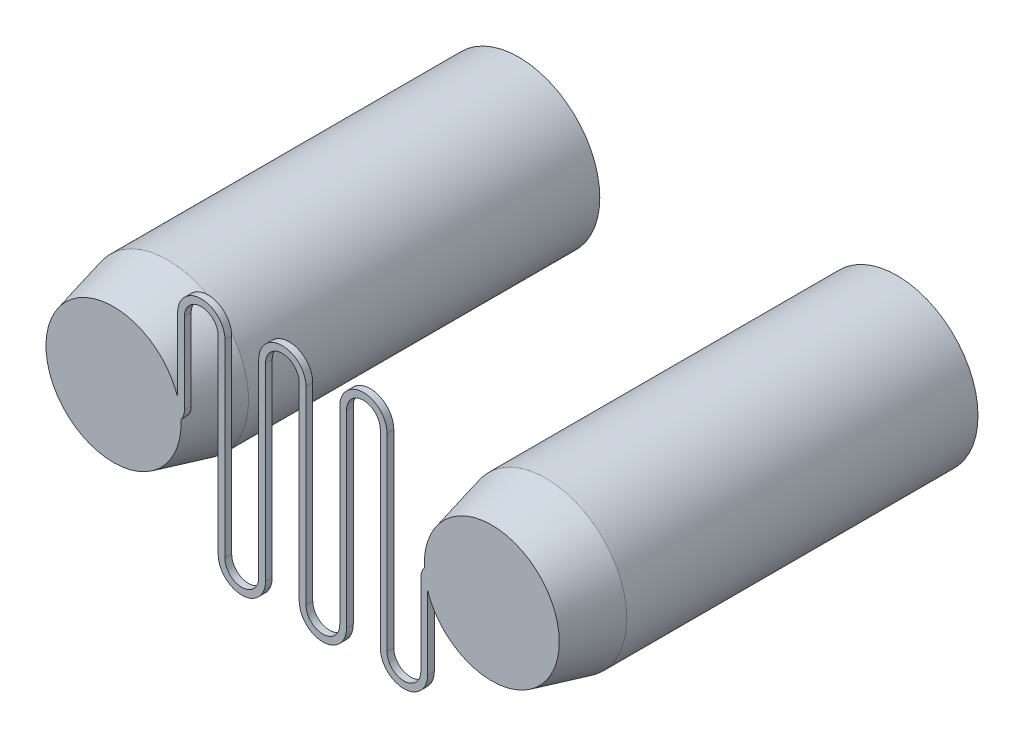
SolidWorks part; units mm, degrees
ref_plane "Front Plane" through (0, 0, 0) normal (0, 0, 1) x (1, 0, 0)
ref_plane "Top Plane" through (0, 0, 0) normal (0, 1, 0) x (1, 0, 0)
ref_plane "Right Plane" through (0, 0, 0) normal (1, 0, 0) x (0, 0, -1)
sketch "Sketch2" plane through (0, 0, 0) normal (0, 0, 1) x (1, 0, 0)
  line L3 (-17.5, -0.25) -> (-13.5, -0.25)
  line L6 (-12.25, 1) -> (-12.25, 7)
  line L9 (-9.75, 7) -> (-9.75, 0)
  line L12 (-9.75, 0) -> (-9.75, -7)
  line L15 (-6.25, -7) -> (-6.25, 0)
  line L18 (-6.25, 0) -> (-6.25, 7)
  line L21 (-3.75, 7) -> (-3.75, 0)
  line L22 (-3.75, 0) -> (-3.75, -7)
  line L23 (-0.25, -7) -> (-0.25, 0)
  line L24 (-0.25, 0) -> (-0.25, 7)
  line L25 (2.25, 7) -> (2.25, 0)
  line L26 (2.25, 0) -> (2.25, -7)
  line L27 (5.75, -7) -> (5.75, -1)
  line L28 (6.5, -0.25) -> (10.5, -0.25)
  line L29 (-17.5, 0.25) -> (-13.5, 0.25)
  line L30 (-12.75, 1) -> (-12.75, 7)
  line L31 (-9.25, 7) -> (-9.25, 0)
  line L32 (-9.25, 0) -> (-9.25, -7)
  line L33 (-6.75, -7) -> (-6.75, 0)
  line L34 (-6.75, 0) -> (-6.75, 7)
  line L35 (-3.25, 7) -> (-3.25, 0)
  line L36 (-3.25, 0) -> (-3.25, -7)
  line L37 (-0.75, -7) -> (-0.75, 0)
  line L38 (-0.75, 0) -> (-0.75, 7)
  line L39 (2.75, 7) -> (2.75, 0)
  line L40 (2.75, 0) -> (2.75, -7)
  line L41 (5.25, -7) -> (5.25, -1)
  line L42 (6.5, 0.25) -> (10.5, 0.25)
  arc A0 (-17.5, 0.25) -> (-17.5, -0.25) centre (-17.5, 0) ccw
  arc A8 (-12.25, 1) -> (-13.5, -0.25) centre (-13.5, 1) cw
  arc A9 (-12.25, 7) -> (-9.75, 7) centre (-11, 7) cw
  arc A10 (-9.75, -7) -> (-6.25, -7) centre (-8, -7) ccw
  arc A11 (-6.25, 7) -> (-3.75, 7) centre (-5, 7) cw
  arc A12 (-3.75, -7) -> (-0.25, -7) centre (-2, -7) ccw
  arc A13 (-0.25, 7) -> (2.25, 7) centre (1, 7) cw
  arc A14 (2.25, -7) -> (5.75, -7) centre (4, -7) ccw
  arc A15 (5.75, -1) -> (6.5, -0.25) centre (6.5, -1) cw
  arc A16 (-12.75, 1) -> (-13.5, 0.25) centre (-13.5, 1) cw
  arc A17 (-12.75, 7) -> (-9.25, 7) centre (-11, 7) cw
  arc A18 (-9.25, -7) -> (-6.75, -7) centre (-8, -7) ccw
  arc A19 (-6.75, 7) -> (-3.25, 7) centre (-5, 7) cw
  arc A20 (-3.25, -7) -> (-0.75, -7) centre (-2, -7) ccw
  arc A21 (-0.75, 7) -> (2.75, 7) centre (1, 7) cw
  arc A22 (2.75, -7) -> (5.25, -7) centre (4, -7) ccw
  arc A23 (5.25, -1) -> (6.5, 0.25) centre (6.5, -1) cw
  arc A24 (10.5, -0.25) -> (10.5, 0.25) centre (10.5, 0) ccw
  point P4 (0, 0)
  point P32 (5.5, 0)
  point P35 (-12.5, 0)
  dimension "D14" = 5
extrude "Boss-Extrude1" add sketch "Sketch2" along normal blind 0.5
ref_plane "Plane1" through (0, 0, 0) normal (0, -1, 0) x (-1, 0, 0)
sketch "Sketch3" plane through (0, 0, 0) normal (0, -1, 0) x (-1, 0, 0)
  line L0 (17.5, -0.5) -> (22.5, -0.5)
  line L2 (17.5, -0.5) -> (17.5, 29.5)
  line L3 (17.5, 29.5) -> (23.5, 29.5)
  line L4 (23.5, 29.5) -> (23.5, 3.5)
  line L5 (23.5, 3.5) -> (22.5, -0.5)
  dimension "D1" = 5
  dimension "D3" = 6
  dimension "D4" = 30
revolve "Revolve1" add sketch "Sketch3" angle 360 about L2
ref_plane "Plane2" through (0, 0, 0) normal (0, -1, 0) x (-1, 0, 0)
sketch "Sketch4" plane through (0, 0, 0) normal (0, -1, 0) x (-1, 0, 0)
  line L0 (-10.5, -0.5) -> (-15.5, -0.5)
  line L2 (-10.5, -0.5) -> (-10.5, 29.5)
  line L3 (-10.5, 29.5) -> (-16.5, 29.5)
  line L4 (-16.5, 29.5) -> (-16.5, 3.5)
  line L5 (-16.5, 3.5) -> (-15.5, -0.5)
  dimension "D1" = 5
  dimension "D3" = 30
  dimension "D4" = 6
revolve "Revolve2" add sketch "Sketch4" angle 360 about L2
sketch "Sketch5" plane through (0, 0, -29.5) normal (0, 0, -1) x (-1, 0, 0)
  circle A0 centre (-10.5, 0) radius 5
  circle A1 centre (17.5, 0) radius 5
  dimension "D1" = 10
  dimension "D2" = 10
extrude "Cut-Extrude1" cut sketch "Sketch5" against normal blind 27
